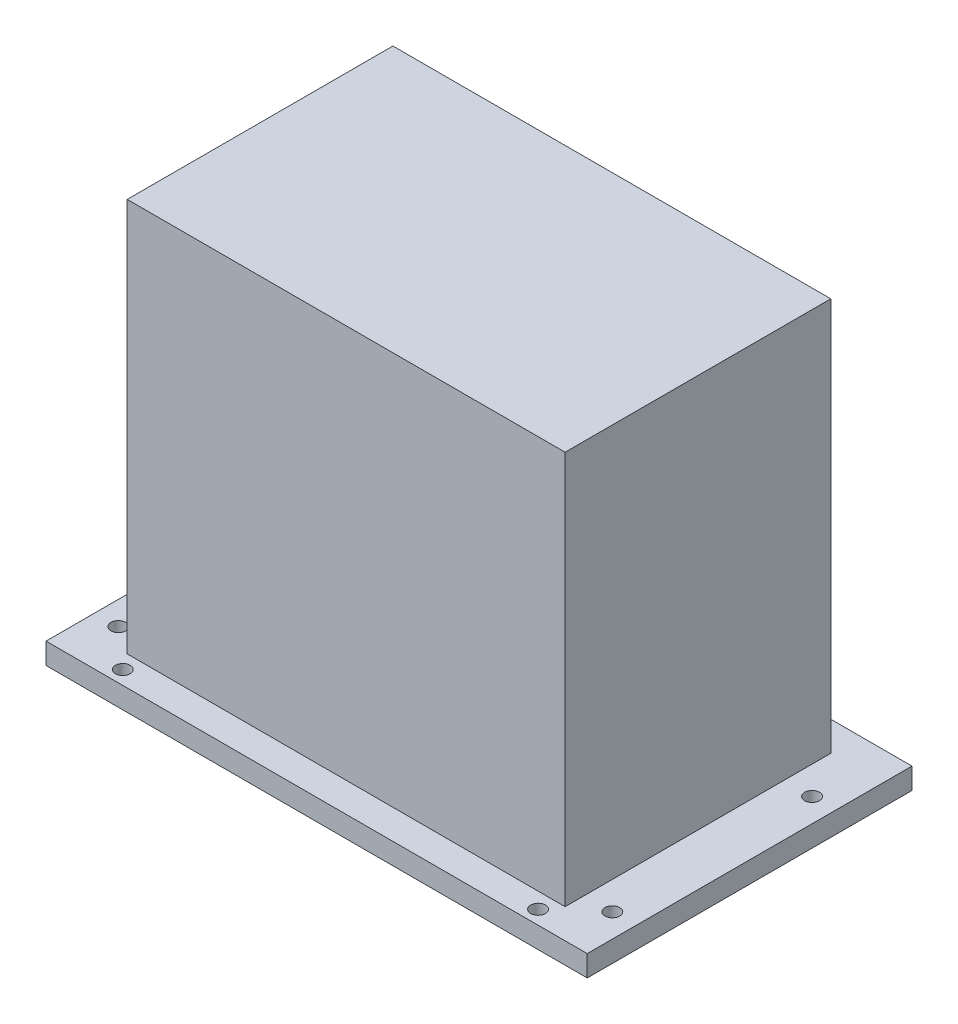
SolidWorks part; units mm, degrees
ref_plane "Front Plane" through (0, 0, 0) normal (0, 0, 1) x (1, 0, 0)
ref_plane "Top Plane" through (0, 0, 0) normal (0, 1, 0) x (1, 0, 0)
ref_plane "Right Plane" through (0, 0, 0) normal (1, 0, 0) x (0, 0, -1)
sketch "Sketch1" plane through (0, 0, 0) normal (0, 1, 0) x (1, 0, 0)
  line L0 (-35.5, 33) -> (-15.5, 33)
  line L1 (-55, -33) -> (55, -33)
  line L2 (-55, -33) -> (-55, 33)
  line L3 (-55, 33) -> (55, 33)
  line L4 (55, -33) -> (55, 33)
  line L5 (-55, -33) -> (55, 33) construction
  line L6 (-55, 33) -> (55, -33) construction
  line L7 (-35.5, 33) -> (-35.5, 27)
  line L8 (-15.5, 33) -> (-15.5, 27)
  line L9 (-35.5, 27) -> (-15.5, 27)
  line L10 (0, -55) -> (0, 55) construction
  line L11 (15.5, 33) -> (15.5, 27)
  line L12 (35.5, 27) -> (15.5, 27)
  line L13 (35.5, 33) -> (35.5, 27)
  line L14 (35.5, 33) -> (15.5, 33)
  circle A0 centre (50.2, 17.5) radius 1.5
  circle A1 centre (50.2, -23.1) radius 1.5
  circle A2 centre (42.2, 24.5) radius 1.5
  circle A3 centre (42.2, 18.5) radius 1.5
  circle A4 centre (42.2, -30.2) radius 1.5
  circle A5 centre (42.2, -24.2) radius 1.5
  circle A6 centre (-42.2, 24.5) radius 1.5
  circle A7 centre (-50.2, 17.5) radius 1.5
  circle A8 centre (-42.2, 18.5) radius 1.5
  circle A9 centre (-42.2, -30.2) radius 1.5
  circle A10 centre (-50.2, -23.1) radius 1.5
  circle A11 centre (-42.2, -24.2) radius 1.5
  point P0 (0, 0)
  dimension "D6" = 3
  dimension "D9" = 9.9
  dimension "D13" = 3
  dimension "D1" = 66
  dimension "D2" = 110
  dimension "D3" = 6
  dimension "D4" = 20
  dimension "D5" = 19.5
  dimension "D7" = 4.8
  dimension "D8" = 15.5
  dimension "D10" = 8.5
  dimension "D11" = 8
  dimension "D12" = 6
  dimension "D14" = 2.8
  dimension "D15" = 6
extrude "Boss-Extrude1" add sketch "Sketch1" along normal blind 4.3 contours L3 L13 L12 L11 L8 L9 L7 L2 L1 L4 A10 A8 A6 A5 A4 A3 A2 A1 A0 A7 A9 A11
sketch "Sketch2" plane through (0, 4.3, 0) normal (0, 1, 0) x (1, 0, 0)
  line L1 (-44.5, -27) -> (44.5, -27)
  line L2 (-44.5, -27) -> (-44.5, 27)
  line L3 (-44.5, 27) -> (44.5, 27)
  line L4 (44.5, -27) -> (44.5, 27)
  line L5 (-44.5, -27) -> (44.5, 27) construction
  line L6 (-44.5, 27) -> (44.5, -27) construction
  point P0 (0, 0)
  dimension "D1" = 89
  dimension "D2" = 54
extrude "Boss-Extrude2" add sketch "Sketch2" along normal blind 80
